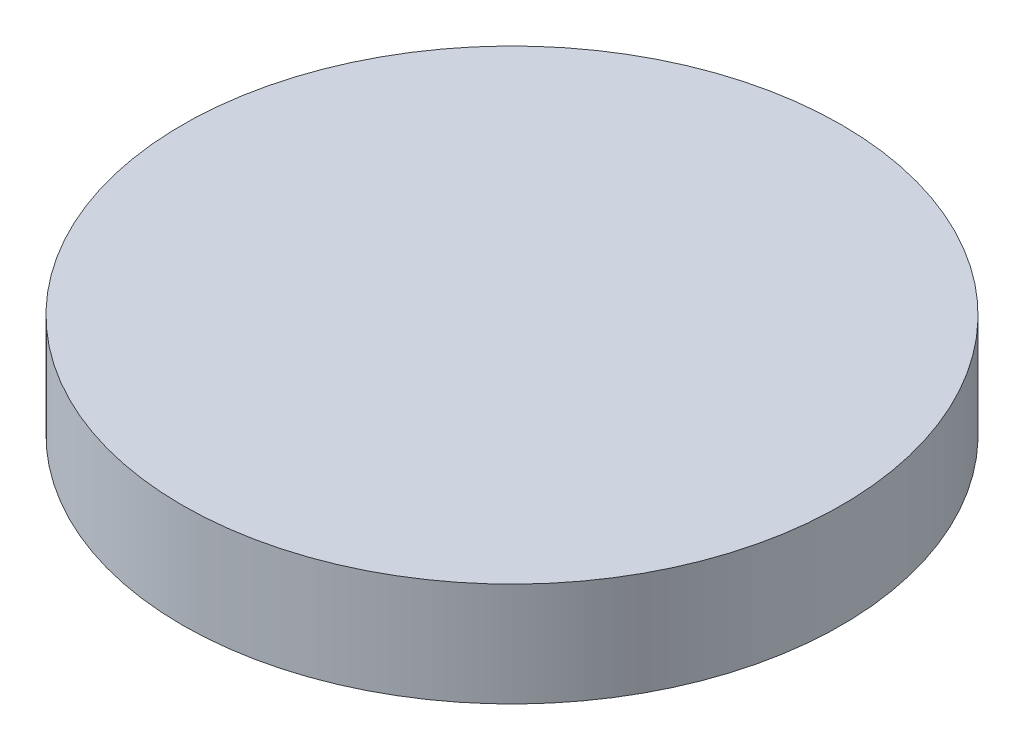
SolidWorks part; units mm, degrees
ref_plane "Front Plane" through (0, 0, 0) normal (0, 0, 1) x (1, 0, 0)
ref_plane "Top Plane" through (0, 0, 0) normal (0, 1, 0) x (1, 0, 0)
ref_plane "Right Plane" through (0, 0, 0) normal (1, 0, 0) x (0, 0, -1)
sketch "Sketch1" plane through (0, 0, 0) normal (0, 1, 0) x (1, 0, 0)
  circle A0 centre (0, 0) radius 6.35
  dimension "D1" = 12.7
extrude "Boss-Extrude1" add sketch "Sketch1" along normal blind 2
